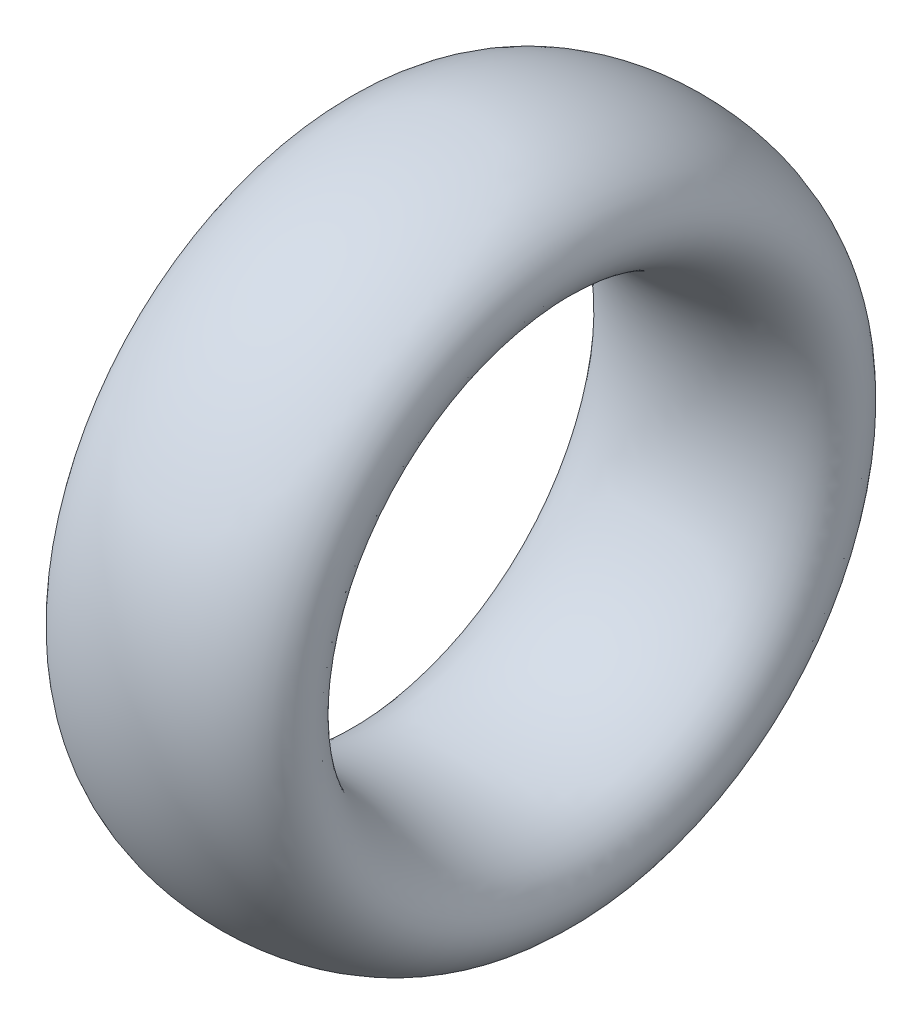
SolidWorks part; units mm, degrees
ref_plane "Přední rovina" through (0, 0, 0) normal (0, 0, 1) x (1, 0, 0)
ref_plane "Vrchní rovina" through (0, 0, 0) normal (0, 1, 0) x (1, 0, 0)
ref_plane "Pravá rovina" through (0, 0, 0) normal (1, 0, 0) x (0, 0, -1)
sketch "Skica1" plane through (0, 0, 0) normal (0, 0, 1) x (1, 0, 0)
  line L0 (0, 0) -> (2.4, 0) construction
  ellipse E0 centre (1.2, 2.65) end of major axis (0, 2.65) minor radius 0.65
  dimension "a" = 1.3
  dimension "b" = 2.4
  dimension "d1" = 4
revolve "Otočit kolem osy1" add sketch "Skica1" angle 360 about L0
